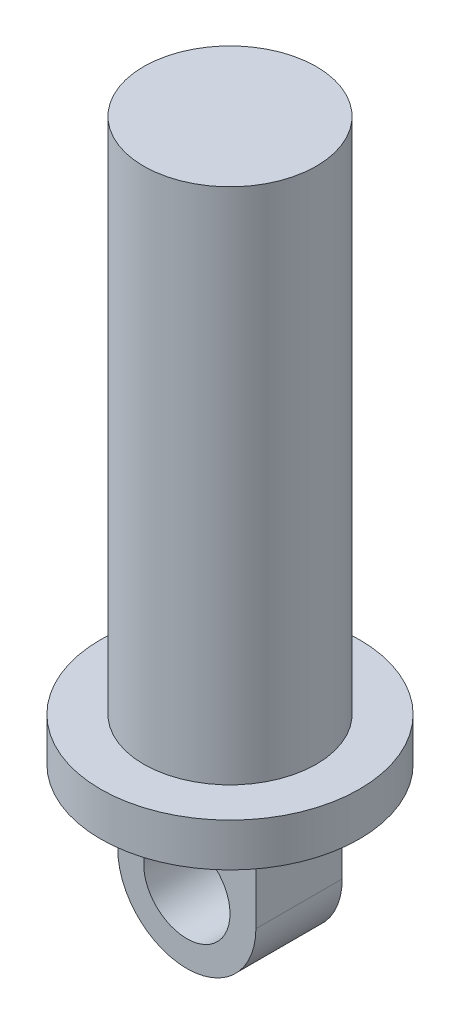
SolidWorks part; units mm, degrees
ref_plane "Front Plane" through (0, 0, 0) normal (0, 0, 1) x (1, 0, 0)
ref_plane "Top Plane" through (0, 0, 0) normal (0, 1, 0) x (1, 0, 0)
ref_plane "Right Plane" through (0, 0, 0) normal (1, 0, 0) x (0, 0, -1)
sketch "Sketch1" plane through (0, 0, 0) normal (0, 0, 1) x (1, 0, 0)
  line L2 (-4, 0) -> (-4, 5)
  line L3 (-4, 5) -> (4, 5)
  line L4 (4, 0) -> (4, 5)
  line L7 (-2.5, 5) -> (2.5, 5)
  circle A0 centre (0, 0) radius 2.5
  arc A1 (-4, 0) -> (4, 0) centre (0, 0) ccw
  dimension "D1" = 5
  dimension "D2" = 8
  dimension "D3" = 5
extrude "Boss-Extrude1" add sketch "Sketch1" along normal mid plane 5 contours L2 A1 L4 L3 A0
sketch "Sketch2" plane through (0, 5, 0) normal (0, 1, 0) x (1, 0, 0)
  circle A0 centre (0, 0) radius 7.5
  dimension "D1" = 15
extrude "Boss-Extrude2" add sketch "Sketch2" along normal blind 2.5
sketch "Sketch3" plane through (0, 7.5, 0) normal (0, 1, 0) x (1, 0, 0)
  circle A0 centre (0, 0) radius 5
  dimension "D1" = 10
extrude "Boss-Extrude3" add sketch "Sketch3" along normal blind 30
